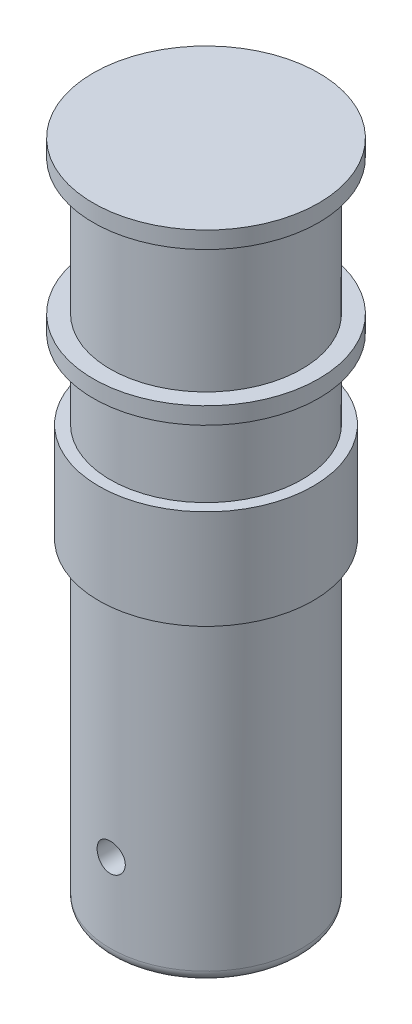
SolidWorks part; units mm, degrees
material "ABS"
ref_plane "Front Plane" through (0, 0, 0) normal (0, 0, 1) x (1, 0, 0)
ref_plane "Top Plane" through (0, 0, 0) normal (0, 1, 0) x (1, 0, 0)
ref_plane "Right Plane" through (0, 0, 0) normal (1, 0, 0) x (0, 0, -1)
sketch "Sketch1" plane through (0, 0, 0) normal (0, 0, 1) x (1, 0, 0)
  line L2 (-8.5, -44) -> (-8.5, -15.8)
  line L3 (-8.5, 0) -> (-10, 0)
  line L4 (-10, 0) -> (-10, 1.5)
  line L5 (-10, 1.5) -> (-8.5, 1.5)
  line L6 (-8.5, 1.5) -> (-8.5, 13.5)
  line L7 (-8.5, 13.5) -> (-10, 13.5)
  line L8 (-10, 13.5) -> (-10, 15)
  line L9 (-10, 15) -> (0, 15)
  line L10 (0, 15) -> (0, -30)
  line L11 (-4, -44) -> (-8.5, -44)
  line L12 (-4, -30) -> (-4, -44)
  line L13 (0, -30) -> (-4, -30)
  line L14 (-8.5, -15.8) -> (-9.5, -15.8)
  line L16 (-9.5, -15.8) -> (-9.5, -7)
  line L17 (-9.5, -7) -> (-8.5, -7)
  line L18 (-8.5, -7) -> (-8.5, 0)
  dimension "D1" = 8.5
  dimension "D2" = 1.5
  dimension "D3" = 44
  dimension "D4" = 1.5
  dimension "D5" = 4
  dimension "D6" = 14
  dimension "D7" = 15
  dimension "D8" = 10
  dimension "D9" = 28.2
  dimension "D10" = 1
  dimension "D11" = 7
revolve "Revolve1" add sketch "Sketch1" angle 360 about L10
fillet "Fillet1" radius 1 2 edges at (-8.5, -44, 0) (-4, -44, 0)
hole_wizard "M3x0.5 Tapped Hole1" positions "Sketch2" profile "Sketch3" tap size "M3x0.5" standard "ANSI Metric"
sketch "Sketch2" plane through (0, 0, 0) normal (0, 0, 1) x (1, 0, 0)
  line L0 (-7.5, -44) -> (7.5, -44) construction
  point P0 (0, -36)
  dimension "D1" = 8
sketch "Sketch3" plane through (0, -36, 0) normal (1, 0, 0) x (0, 1, 0)
  line L0 (0, 0) -> (0, 8.5)
  line L1 (0, 8.5) -> (1.25, 8.5)
  line L2 (1.25, 8.5) -> (1.25, 0)
  line L5 (1.25, 0) -> (0, 0)
  line L11 (0, -6.35) -> (0, 107.95) construction
  dimension "Thru Tap Drill Dia." = 2.5
  dimension "Thru Tap Drill Depth" = 8.5
cosmetic thread "Hole Thread1" parameters "D2"=3
